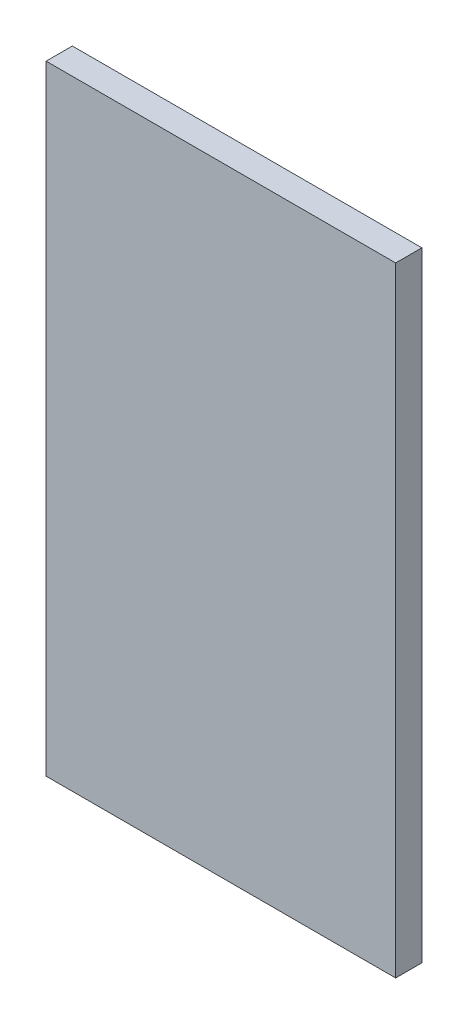
SolidWorks part; units mm, degrees
ref_plane "Front Plane" through (0, 0, 0) normal (0, 0, 1) x (1, 0, 0)
ref_plane "Top Plane" through (0, 0, 0) normal (0, 1, 0) x (1, 0, 0)
ref_plane "Right Plane" through (0, 0, 0) normal (1, 0, 0) x (0, 0, -1)
sketch "Sketch2" plane through (0, 0, 0) normal (0, 1, 0) x (1, 0, 0)
  line L1 (-254, -19.05) -> (254, -19.05)
  line L2 (-254, -19.05) -> (-254, 19.05)
  line L3 (-254, 19.05) -> (254, 19.05)
  line L4 (254, -19.05) -> (254, 19.05)
  line L5 (-254, -19.05) -> (254, 19.05) construction
  line L6 (-254, 19.05) -> (254, -19.05) construction
  point P0 (0, 0)
  dimension "D1" = 508
  dimension "D2" = 38.1
extrude "Boss-Extrude1" add sketch "Sketch2" along normal blind 900
